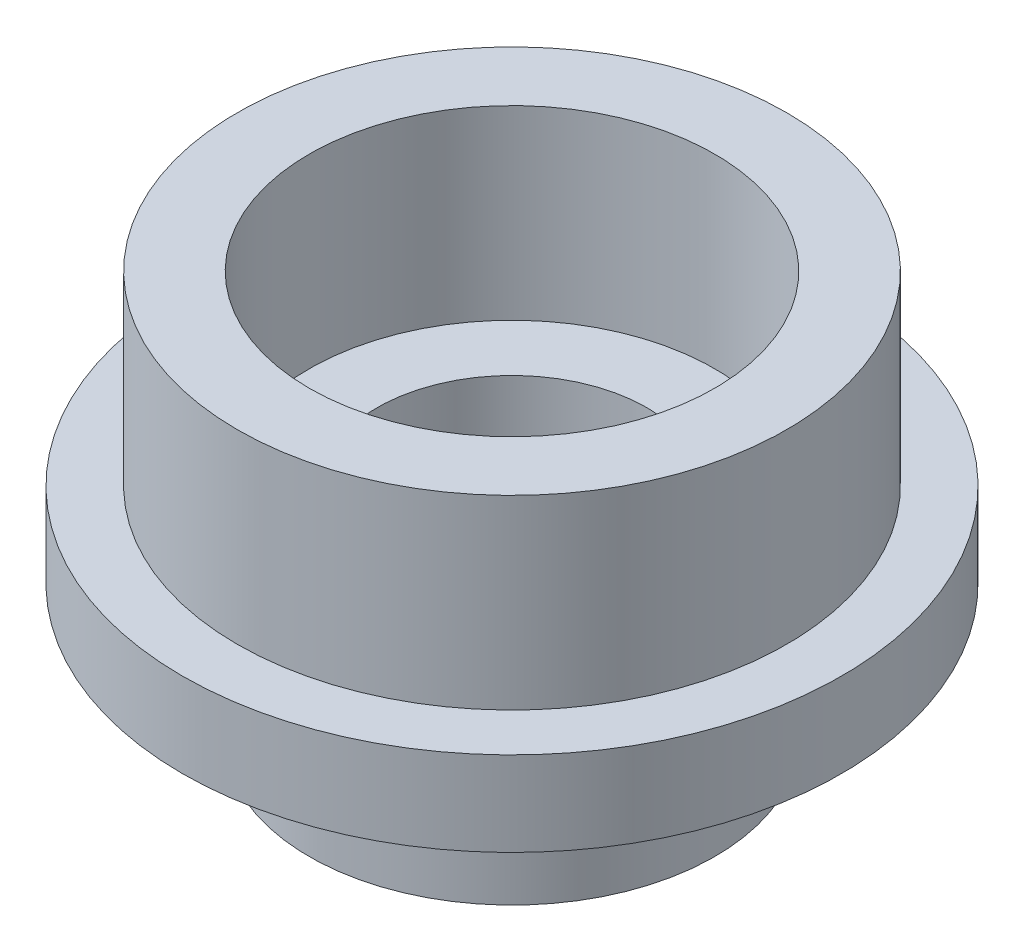
SolidWorks part; units mm, degrees
ref_plane "Front Plane" through (0, 0, 0) normal (0, 0, 1) x (1, 0, 0)
ref_plane "Top Plane" through (0, 0, 0) normal (0, 1, 0) x (1, 0, 0)
ref_plane "Right Plane" through (0, 0, 0) normal (1, 0, 0) x (0, 0, -1)
sketch "Sketch1" plane through (0, 0, 0) normal (0, 1, 0) x (1, 0, 0)
  circle A0 centre (0, 0) radius 2.4
  circle A1 centre (0, 0) radius 3.25
  dimension "D1" = 4.8
  dimension "D2" = 6.5
extrude "Boss-Extrude1" add sketch "Sketch1" along normal blind 2.2
sketch "Sketch2" plane through (0, 0, 0) normal (0, -1, 0) x (1, 0, 0)
  circle A0 centre (0, 0) radius 3.9
  dimension "D1" = 7.8
extrude "Boss-Extrude2" add sketch "Sketch2" along normal blind 1
sketch "Sketch3" plane through (0, -1, 0) normal (0, -1, 0) x (1, 0, 0)
  circle A0 centre (0, 0) radius 2.4
  circle A1 centre (0, 0) radius 1.6
  dimension "D1" = 4.8
  dimension "D2" = 0.8
extrude "Boss-Extrude3" add sketch "Sketch3" along normal blind 1.6
sketch "Sketch4" plane through (0, -1, 0) normal (0, -1, 0) x (1, 0, 0)
  circle A0 centre (0, 0) radius 1.6 construction
  circle A1 centre (0, 0) radius 1.6
extrude "Cut-Extrude1" cut sketch "Sketch4" against normal through all
